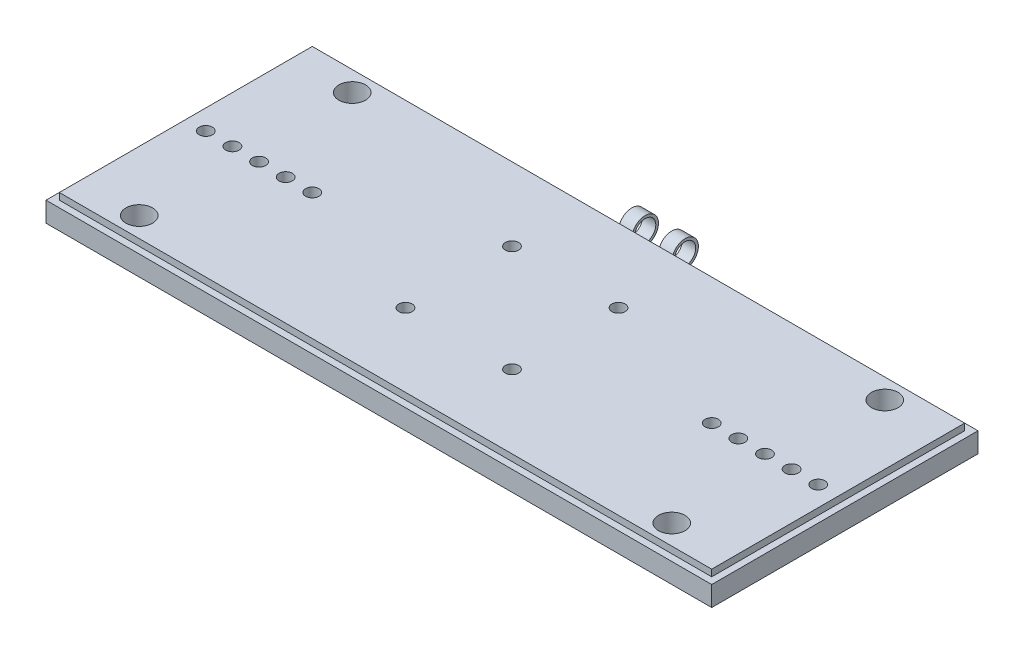
SolidWorks part; units mm, degrees
ref_plane "Front Plane" through (0, 0, 0) normal (0, 0, 1) x (1, 0, 0)
ref_plane "Top Plane" through (0, 0, 0) normal (0, 1, 0) x (1, 0, 0)
ref_plane "Right Plane" through (0, 0, 0) normal (1, 0, 0) x (0, 0, -1)
sketch "Sketch1" plane through (0, 0, 0) normal (0, 1, 0) x (1, 0, 0)
  line L0 (-100, 40) -> (100, 40) construction
  line L1 (-125, -50) -> (125, -50)
  line L2 (-125, -50) -> (-125, 50)
  line L3 (-125, 50) -> (125, 50)
  line L4 (125, -50) -> (125, 50)
  line L5 (-125, -50) -> (125, 50) construction
  line L6 (-125, 50) -> (125, -50) construction
  line L7 (-125, 0) -> (125, 0) construction
  line L8 (0, 50) -> (0, -50) construction
  line L9 (-20, -20) -> (20, -20) construction
  line L10 (-20, -20) -> (-20, 20) construction
  line L11 (-20, 20) -> (20, 20) construction
  line L12 (20, -20) -> (20, 20) construction
  line L13 (-20, -20) -> (20, 20) construction
  line L14 (-20, 20) -> (20, -20) construction
  circle A0 centre (-100, 40) radius 5
  circle A1 centre (100, 40) radius 5
  circle A2 centre (-100, -40) radius 5
  circle A3 centre (100, -40) radius 5
  circle A4 centre (-20, 20) radius 2.5
  circle A5 centre (20, 20) radius 2.5
  circle A6 centre (-20, -20) radius 2.5
  circle A7 centre (20, -20) radius 2.5
  circle A8 centre (-115, 0) radius 2.5
  circle A9 centre (-105, 0) radius 2.5
  circle A10 centre (-95, 0) radius 2.5
  circle A11 centre (-85, 0) radius 2.5
  circle A12 centre (-75, 0) radius 2.5
  circle A13 centre (75, 0) radius 2.5
  circle A14 centre (85, 0) radius 2.5
  circle A15 centre (95, 0) radius 2.5
  circle A16 centre (105, 0) radius 2.5
  circle A17 centre (115, 0) radius 2.5
  point P0 (0, 0)
  point P16 (0, 0)
  dimension "D4" = 10
  dimension "D5" = 10
  dimension "D8" = 5
  dimension "D9" = 5
  dimension "D10" = 5
  dimension "D11" = 5
  dimension "D12" = 5
  dimension "D1" = 250
  dimension "D2" = 100
  dimension "D3" = 10
  dimension "D6" = 40
  dimension "D7" = 40
  dimension "D13" = 10
  dimension "D14" = 5
extrude "Boss-Extrude1" add sketch "Sketch1" along normal mid plane 10
sketch "Sketch2" plane through (0, 0, 0) normal (1, 0, 0) x (0, 0, -1)
  line L0 (47.0525, 5) -> (47.0525, -5) construction
  line L1 (-50, 5) -> (50, 5) construction
  line L2 (-50, -5) -> (50, -5) construction
  line L3 (47.0525, 0) -> (55, 0) construction
  line L4 (50, 5) -> (50, -5) construction
  line L5 (55, -5) -> (50, -5)
  line L6 (50, -5) -> (50, 0)
  arc A0 (55, -5) -> (50, 0) centre (55, 0) ccw
  dimension "D1" = 10
  dimension "D2" = 5
extrude "Boss-Extrude2" add sketch "Sketch2" along normal mid plane 20
sketch "Sketch3" plane through (0, 0, 0) normal (1, 0, 0) x (0, 0, -1)
  line L0 (50, 5) -> (50, -6.0225)
  line L1 (50, -6.0225) -> (64.6378, -7.2704)
  line L2 (64.6378, -7.2704) -> (61.9218, 9.2827)
  line L3 (61.9218, 9.2827) -> (50, 5)
extrude "Cut-Extrude1" cut sketch "Sketch3" against normal mid plane 10
sketch "Sketch4" plane through (10, 0, 0) normal (1, 0, 0) x (0, 0, -1)
  circle A0 centre (55, 0) radius 4
  dimension "D1" = 8
extrude "Cut-Extrude2" cut sketch "Sketch4" against normal mid plane 89
sketch "Sketch5" plane through (125, 0, 0) normal (1, 0, 0) x (0, 0, -1)
  line L0 (0, -5) -> (0, 5) construction
  line L1 (-52.5, 7.5) -> (-47.5, 7.5)
  line L2 (-52.5, 7.5) -> (-52.5, 2.5)
  line L3 (-52.5, 2.5) -> (-47.5, 2.5)
  line L4 (-47.5, 7.5) -> (-47.5, 2.5)
  line L5 (-52.5, 7.5) -> (-47.5, 2.5) construction
  line L6 (-52.5, 2.5) -> (-47.5, 7.5) construction
  line L7 (-50, -5) -> (50, -5) construction
  line L8 (-50, 5) -> (50, 5) construction
  line L9 (50, 5) -> (47.5, 7.5) construction
  line L10 (50, 5) -> (47.5, 2.5) construction
  line L11 (47.5, 7.5) -> (47.5, 2.5)
  line L12 (50, 2.5) -> (47.5, 2.5)
  line L14 (50, 7.5) -> (47.5, 7.5)
  line L15 (50, 7.5) -> (50, 2.5)
  point P0 (-50, 5)
  point P16 (50, 5)
  dimension "D1" = 5
  dimension "D2" = 5
extrude "Cut-Extrude3" cut sketch "Sketch5" against normal mid plane 581
sketch "Sketch6" plane through (0, 0, 0) normal (0, 0, 1) x (1, 0, 0)
  line L0 (-125, 2.5) -> (125, 2.5) construction
  line L1 (127.5, 7.5) -> (122.5, 7.5)
  line L2 (127.5, 7.5) -> (127.5, 2.5)
  line L3 (127.5, 2.5) -> (122.5, 2.5)
  line L4 (122.5, 7.5) -> (122.5, 2.5)
  line L5 (127.5, 7.5) -> (122.5, 2.5) construction
  line L6 (127.5, 2.5) -> (122.5, 7.5) construction
  line L7 (0, 5) -> (0, -5) construction
  line L8 (-125, 5) -> (125, 5) construction
  line L9 (-125, -5) -> (125, -5) construction
  line L10 (-127.5, 2.5) -> (-122.5, 7.5) construction
  line L11 (-127.5, 7.5) -> (-122.5, 2.5) construction
  line L12 (-122.5, 7.5) -> (-122.5, 2.5)
  line L13 (-127.5, 2.5) -> (-122.5, 2.5)
  line L14 (-127.5, 7.5) -> (-127.5, 2.5)
  line L15 (-127.5, 7.5) -> (-122.5, 7.5)
  point P0 (125, 5)
  point P18 (-125, 5)
  dimension "D1" = 5
extrude "Cut-Extrude4" cut sketch "Sketch6" against normal mid plane 581
